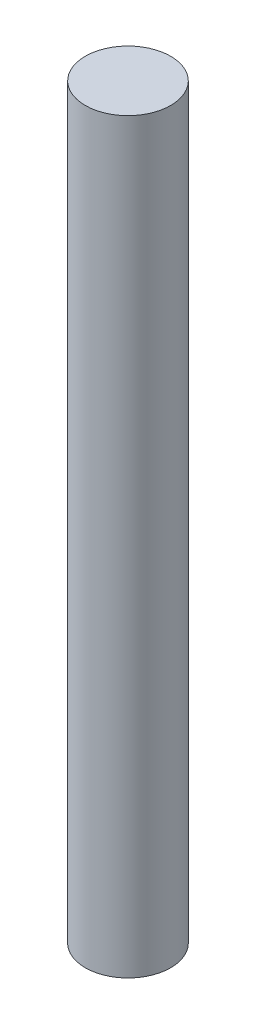
SolidWorks part; units mm, degrees
ref_plane "Front Plane" through (0, 0, 0) normal (0, 0, 1) x (1, 0, 0)
ref_plane "Top Plane" through (0, 0, 0) normal (0, 1, 0) x (1, 0, 0)
ref_plane "Right Plane" through (0, 0, 0) normal (1, 0, 0) x (0, 0, -1)
sketch "Sketch1" plane through (0, 0, 0) normal (0, 1, 0) x (1, 0, 0)
  circle A0 centre (0, 0) radius 2
  dimension "D1" = 4
extrude "Boss-Extrude1" add sketch "Sketch1" along normal blind 35
